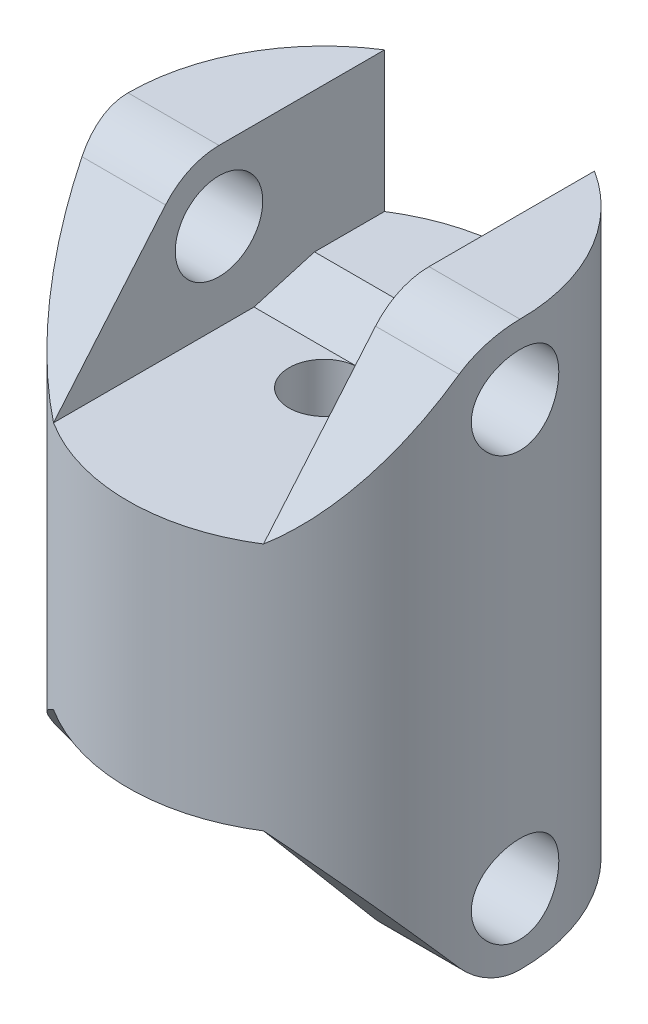
SolidWorks part; units mm, degrees
ref_plane "Front Plane" through (0, 0, 0) normal (0, 0, 1) x (1, 0, 0)
ref_plane "Top Plane" through (0, 0, 0) normal (0, 1, 0) x (1, 0, 0)
ref_plane "Right Plane" through (0, 0, 0) normal (1, 0, 0) x (0, 0, -1)
sketch "Sketch1" plane through (0, 0, 0) normal (0, 1, 0) x (1, 0, 0)
  circle A0 centre (0, 0) radius 14.224
  dimension "D1" = 28.448
extrude "Boss-Extrude1" add sketch "Sketch1" along normal blind 40.894
sketch "Sketch2" plane through (0, 40.894, 0) normal (0, 1, 0) x (1, 0, 0)
  line L0 (7.62, 12.0107) -> (7.62, -12.0107)
  line L1 (-7.62, 12.0107) -> (-7.62, -12.0107)
  arc A0 (-7.62, -12.0107) -> (7.62, -12.0107) centre (0, 0) ccw
  arc A1 (7.62, 12.0107) -> (-7.62, 12.0107) centre (0, 0) ccw
  dimension "D2" = 28.448
  dimension "D1" = 7.62
  dimension "D3" = 7.62
extrude "Cut-Extrude1" cut sketch "Sketch2" against normal blind 11.43
sketch "Sketch3" plane through (0, 0, 0) normal (0, -1, 0) x (1, 0, 0)
  line L4 (-7.62, 12.0107) -> (-7.62, -12.0107)
  line L5 (7.62, 12.0107) -> (7.62, -12.0107)
  arc A4 (-7.62, -12.0107) -> (7.62, -12.0107) centre (0, 0) ccw
  arc A5 (7.62, 12.0107) -> (-7.62, 12.0107) centre (0, 0) ccw
  dimension "D1" = 7.62
  dimension "D3" = 28.448
  dimension "D2" = 7.62
extrude "Cut-Extrude2" cut sketch "Sketch3" against normal blind 11.43
sketch "Sketch4" plane through (-7.62, 0, 0) normal (1, 0, 0) x (0, 0, -1)
  line L0 (12.0107, 40.894) -> (-12.0107, 40.894) construction
  line L7 (-3.8814, 39.0914) -> (-12.0107, 29.464)
  line L8 (-12.0107, 29.464) -> (-12.0107, 40.894)
  line L9 (-12.0107, 40.894) -> (0, 40.894)
  line L10 (-3.8814, 1.8026) -> (-12.0107, 11.43)
  line L11 (-12.0107, 11.43) -> (-12.0107, 0)
  line L12 (-12.0107, 0) -> (0, 0)
  line L13 (-12.0107, 0) -> (12.0107, 0) construction
  circle A0 centre (0, 35.814) radius 3.175
  circle A2 centre (0, 5.08) radius 3.175
  arc A4 (0, 40.894) -> (-3.8814, 39.0914) centre (0, 35.814) ccw
  arc A5 (0, 0) -> (-3.8814, 1.8026) centre (0, 5.08) cw
  dimension "D1" = 6.35
  dimension "D3" = 6.35
  dimension "D5" = 0
  dimension "D2" = 5.08
  dimension "D4" = 5.08
extrude "Cut-Extrude3" cut sketch "Sketch4" against normal through all both and the other way through all
sketch "Sketch5" plane through (0, 29.464, 0) normal (0, 1, 0) x (1, 0, 0)
  circle A0 centre (0, 0) radius 2.54
  dimension "D1" = 5.08
extrude "Cut-Extrude4" cut sketch "Sketch5" against normal through all
sketch "Sketch6" plane through (-7.62, 0, 0) normal (1, 0, 0) x (0, 0, -1)
  line L0 (2.54, 29.464) -> (12.0107, 29.464)
  line L1 (12.0107, 29.464) -> (-12.0107, 29.464) construction
  line L2 (12.0107, 29.464) -> (12.0107, 30.734)
  line L3 (12.0107, 29.464) -> (12.0107, 40.894) construction
  line L4 (12.0107, 30.734) -> (6.9307, 30.734)
  line L5 (6.9307, 30.734) -> (2.54, 29.464)
  point P8 (0, 29.464)
  dimension "D2" = 5.08
  dimension "D1" = 2.54
  dimension "D3" = 1.27
extrude "Boss-Extrude2" add sketch "Sketch6" along normal up to surface (15.24 mm away) up to face at (7.62, 35.814, -3.175)
sketch "Sketch7" plane through (0, 29.464, 0) normal (0, 1, 0) x (1, 0, 0)
  line L0 (-7.62, 12.0107) -> (7.62, 12.0107)
  arc A0 (-7.62, 12.0107) -> (7.62, 12.0107) centre (0, 0) cw
  arc A1 (7.62, 12.0107) -> (-7.62, 12.0107) centre (0, 0) ccw construction
  arc M1 (7.62, 12.0107) -> (-7.62, 12.0107) centre (0, 0) ccw
  line M2 (-7.62, 12.0107) -> (7.62, 12.0107)
extrude "Boss-Extrude3" add sketch "Sketch7" along normal up to surface (1.27 mm away) contours M2 M1 up to face at (0, 30.734, -9.4707)
